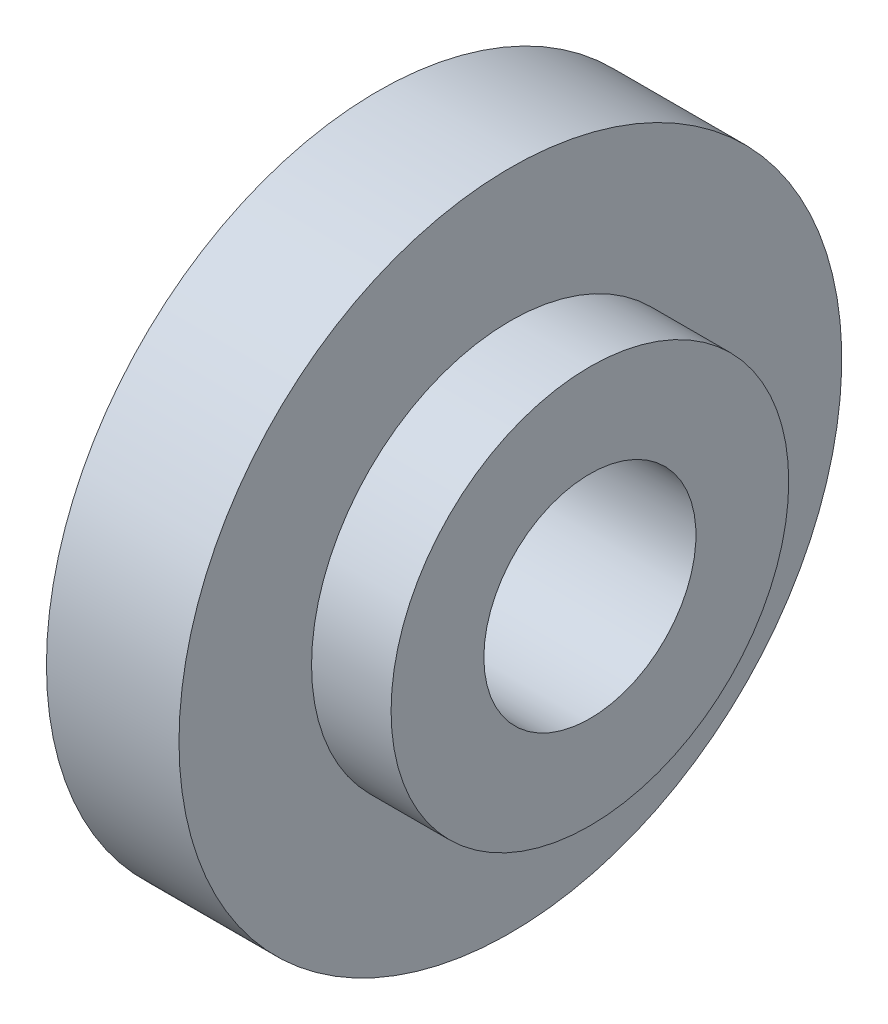
SolidWorks part; units mm, degrees
ref_plane "前视基准面" through (0, 0, 0) normal (0, 0, 1) x (1, 0, 0)
ref_plane "上视基准面" through (0, 0, 0) normal (0, 1, 0) x (1, 0, 0)
ref_plane "右视基准面" through (0, 0, 0) normal (1, 0, 0) x (0, 0, -1)
sketch "草图1" plane through (0, 0, 0) normal (0, 1, 0) x (1, 0, 0)
  line L0 (0, 0) -> (72.9971, 0) construction
  line L1 (0, 4) -> (0, 12.5)
  line L2 (0, 12.5) -> (5, 12.5)
  line L3 (5, 12.5) -> (5, 7.5)
  line L4 (5, 7.5) -> (8, 7.5)
  line L5 (8, 7.5) -> (8, 4)
  line L6 (8, 4) -> (0, 4)
  dimension "D1" = 12.5
  dimension "D2" = 5
  dimension "D3" = 3
  dimension "D4" = 7.5
  dimension "D5" = 4
revolve "旋转1" add sketch "草图1" angle 360 about L0
